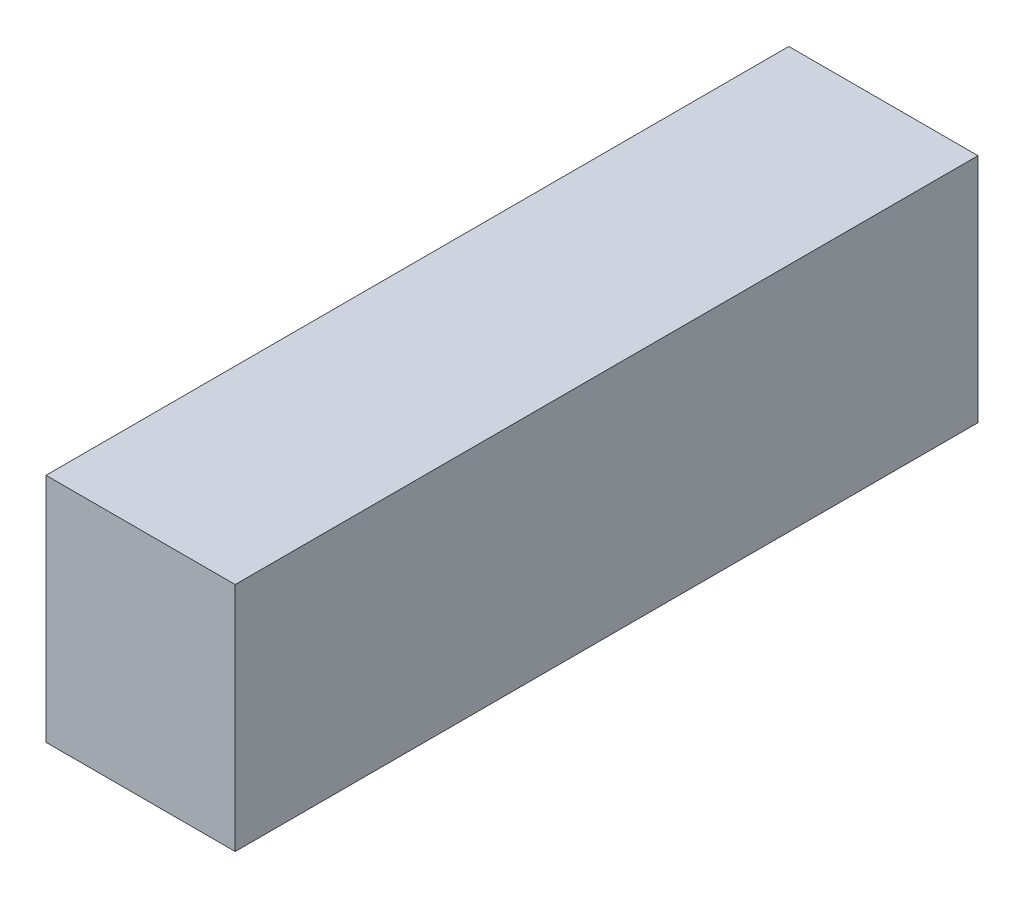
SolidWorks part; units mm, degrees
ref_plane "Front" through (0, 0, 0) normal (0, 0, 1) x (1, 0, 0)
ref_plane "Top" through (0, 0, 0) normal (0, 1, 0) x (1, 0, 0)
ref_plane "Right" through (0, 0, 0) normal (1, 0, 0) x (0, 0, -1)
ref_plane "Plane1" through (0, -15, 0) normal (0, -1, 0) x (1, 0, 0)
sketch "Sketch1" plane through (0, -15, 0) normal (0, -1, 0) x (1, 0, 0)
  line L0 (6, 30) -> (6, 136)
  line L1 (6, 136) -> (-21, 136)
  line L2 (-21, 136) -> (-21, 30)
  line L3 (-21, 30) -> (6, 30)
  dimension "D1" = 27
  dimension "D2" = 106
extrude "Boss-Extrude1" add sketch "Sketch1" against normal blind 33
